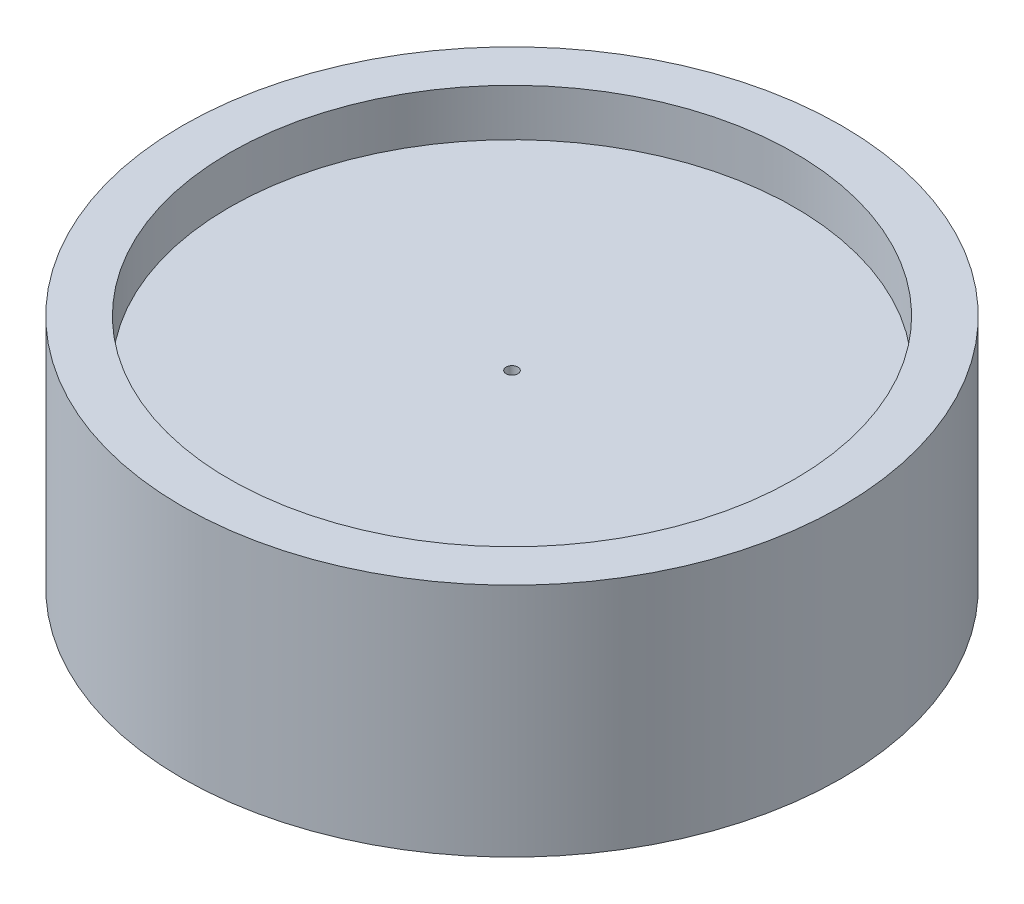
SolidWorks part; units mm, degrees
ref_plane "Front Plane" through (0, 0, 0) normal (0, 0, 1) x (1, 0, 0)
ref_plane "Top Plane" through (0, 0, 0) normal (0, 1, 0) x (1, 0, 0)
ref_plane "Right Plane" through (0, 0, 0) normal (1, 0, 0) x (0, 0, -1)
sketch "Sketch2" plane through (0, 0, 0) normal (0, 0, 1) x (1, 0, 0)
  line L0 (0, 0) -> (48, 0)
  line L1 (48, 0) -> (48, 8)
  line L2 (48, 8) -> (56, 8)
  line L3 (56, 8) -> (56, -32)
  line L4 (56, -32) -> (48, -32)
  line L5 (48, -32) -> (48, -12)
  line L6 (48, -12) -> (0, -12)
  line L7 (0, -12) -> (0, 0)
  dimension "D1" = 48
  dimension "D2" = 20
  dimension "D3" = 40
  dimension "D4" = 8
  dimension "D5" = 12
revolve "Blade Casing Revolve" add sketch "Sketch2" angle 360 about L7
sketch "Sketch3" plane through (0, 0, 0) normal (0, 1, 0) x (1, 0, 0)
  circle A0 centre (0, 0) radius 1
  dimension "D1" = 2
extrude "Hole for Screw (Blade Case)" cut sketch "Sketch3" against normal blind 100
ref_plane "Casing Plane" through (0, 0, 0) normal (0, 0, 1) x (1, 0, 0)
